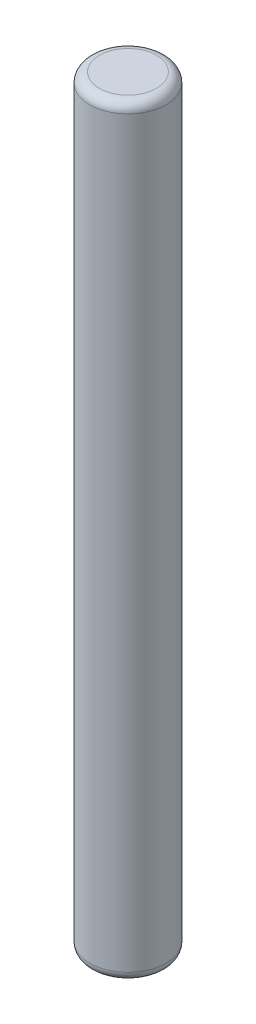
SolidWorks part; units mm, degrees
ref_plane "前视基准面" through (0, 0, 0) normal (0, 0, 1) x (1, 0, 0)
ref_plane "上视基准面" through (0, 0, 0) normal (0, 1, 0) x (1, 0, 0)
ref_plane "右视基准面" through (0, 0, 0) normal (1, 0, 0) x (0, 0, -1)
sketch "草图1" plane through (0, 0, 0) normal (0, 1, 0) x (1, 0, 0)
  circle A0 centre (0, 0) radius 2
  dimension "D1" = 4
extrude "凸台-拉伸1" add sketch "草图1" along normal blind 40
fillet "圆角1" radius 0.5 2 edges at (0, 0, 2) (0, 40, 2)
